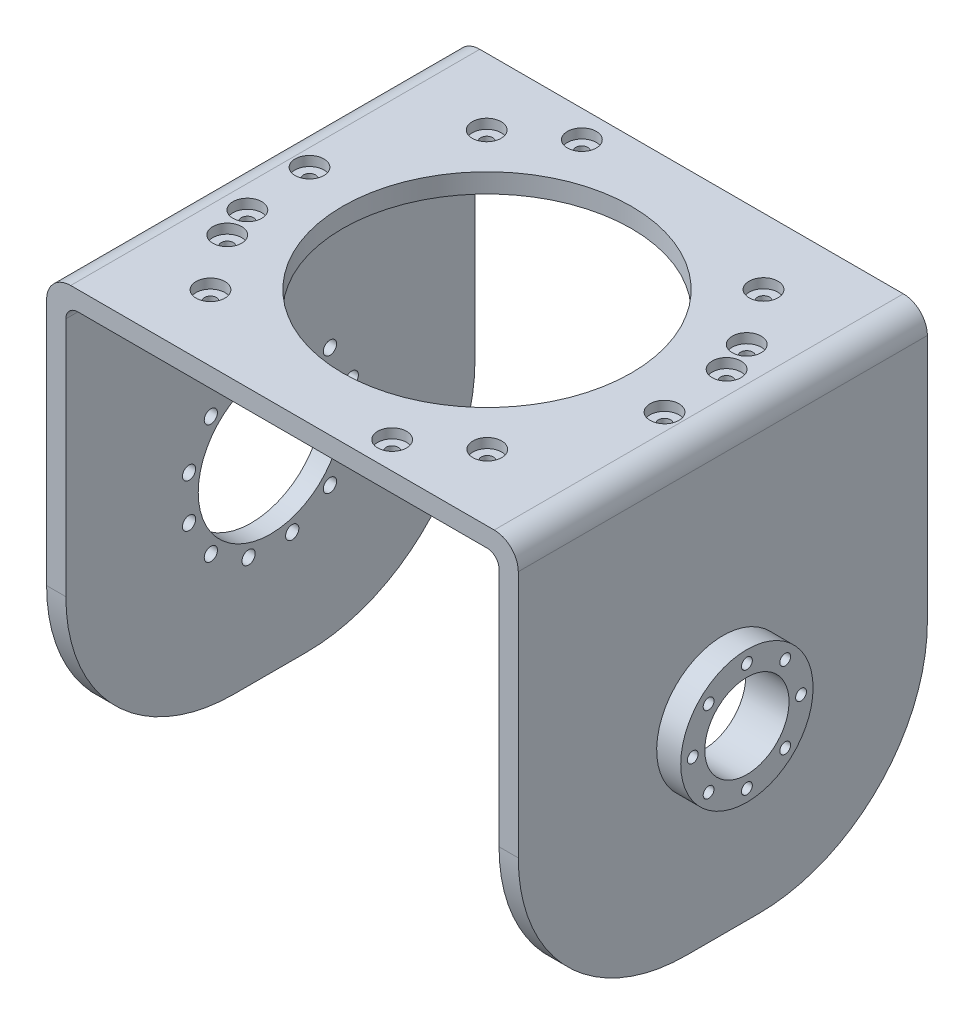
SolidWorks part; units mm, degrees
material "6061 合金"
ref_plane "前视基准面" through (0, 0, 0) normal (0, 0, 1) x (1, 0, 0)
ref_plane "上视基准面" through (0, 0, 0) normal (0, 1, 0) x (1, 0, 0)
ref_plane "右视基准面" through (0, 0, 0) normal (1, 0, 0) x (0, 0, -1)
other "Configuration Table"
sketch "草图1" plane through (0, 0, 0) normal (0, 0, 1) x (1, 0, 0)
  line L0 (-180, 0) -> (0, 0)
  line L1 (0, 0) -> (0, -175)
  line L3 (8, -175) -> (8, 8)
  line L4 (8, 8) -> (-180, 8)
  line L6 (0, -175) -> (8, -175)
  line L12 (-180, 8) -> (-188, 8)
  line L13 (-180, 0) -> (-180, -175)
  line L14 (-180, -175) -> (-188, -175)
  line L15 (-188, 8) -> (-188, -175)
  dimension "D1" = 8
  dimension "D2" = 8
  dimension "D4" = 180
  dimension "D5" = 183
  dimension "D6" = 8
  dimension "D8" = 8
extrude "凸台-拉伸1" add sketch "草图1" along normal blind 170
sketch "草图2" plane through (0, 8, 0) normal (0, 1, 0) x (1, 0, 0)
  line L0 (-216.3195, -85) -> (51.5119, -85) construction
  line L1 (8, -170) -> (-188, -170) construction
  line L2 (8, 0) -> (-188, 0) construction
  line L7 (-90, -75.3242) -> (-90, -92.2023) construction
  line L8 (8, -170) -> (8, 0) construction
  line L9 (-188, -170) -> (-188, 0) construction
  circle A2 centre (-90, -85) radius 60
  dimension "D3" = 120
extrude "切除-拉伸1" cut sketch "草图2" against normal blind 180 contours A2 L0 | L0 A2
sketch "草图3" plane through (8, 0, 0) normal (1, 0, 0) x (0, 0, -1)
  line L0 (-85, 25.6845) -> (-85, -173.3318) construction
  line L1 (0, -175) -> (0, 8) construction
  line L2 (-170, -175) -> (-170, 8) construction
  line L3 (-170, -175) -> (0, -175) construction
  line L4 (0, 0) -> (-209.686, 0) construction
  circle A0 centre (-85, -95) radius 17.5
  dimension "D1" = 35
  dimension "D2" = 80
extrude "切除-拉伸2" cut sketch "草图3" against normal through all both and the other way through all contours A0
fillet "圆角1" radius 70 4 edges at (-184, -175, 170) (-184, -175, 0) (4, -175, 0) (4, -175, 170)
fillet "圆角2" radius 5 2 edges at (-180, 0, 85) (0, 0, 85)
fillet "圆角3" radius 10 2 edges at (8, 8, 85) (-188, 8, 85)
sketch "草图6" plane through (-188, 0, 0) normal (-1, 0, 0) x (0, 0, 1)
  circle A0 centre (85, -95) radius 30
  dimension "D1" = 60
extrude "切除-拉伸6" cut sketch "草图6" against normal blind 39
sketch "草图7" plane through (0, 0, 0) normal (-1, 0, 0) x (0, 0, 1)
  circle A0 centre (85, -95) radius 13
  dimension "D1" = 26
extrude "切除-拉伸7" [suppressed] cut sketch "草图7" against normal blind 0.7
sketch "草图8" plane through (8, 0, 0) normal (1, 0, 0) x (0, 0, -1)
  line L0 (-85, -95) -> (-13.3452, -95) construction
  line L1 (-85, -95) -> (-143.0331, -95) construction
  circle A0 centre (-55, -95) radius 2.5
  circle A1 centre (-115, -95) radius 2.5
  dimension "D1" = 5
  dimension "D2" = 5
  dimension "D3" = 30
  dimension "D4" = 30
extrude "切除-拉伸8" [suppressed] cut sketch "草图8" against normal blind 10
sketch "草图9" [suppressed] plane through (8, 0, 0) normal (1, 0, 0) x (0, 0, -1)
  circle A0 centre (-55, -95) radius 6
  circle A1 centre (-115, -95) radius 6
  dimension "D1" = 12
  dimension "D2" = 12
extrude "切除-拉伸9" [suppressed] cut sketch "草图9" against normal blind 4
sketch "草图10" plane through (0, 0, 0) normal (0, -1, 0) x (1, 0, 0)
  arc A0 (-173.1989, 76.7742) -> (-168.6673, 78.8872) centre (-170.9331, 77.8307) ccw construction
  arc A1 (-149.7806, 26.5535) -> (-145.249, 28.6665) centre (-147.5148, 27.61) ccw construction
  arc A2 (-126.5235, 10.2687) -> (-121.992, 12.3818) centre (-124.2577, 11.3252) ccw construction
  arc A3 (-113.38, 5.4849) -> (-108.8485, 7.598) centre (-111.1143, 6.5414) ccw construction
  arc A4 (-85.0965, 3.0104) -> (-80.5649, 5.1235) centre (-82.8307, 4.0669) ccw construction
  arc A5 (-34.8758, 26.4287) -> (-30.3442, 28.5418) centre (-32.61, 27.4852) ccw construction
  arc A6 (-13.8072, 62.8292) -> (-9.2756, 64.9423) centre (-11.5414, 63.8857) ccw construction
  arc A7 (-18.591, 49.6857) -> (-14.0595, 51.7988) centre (-16.3252, 50.7423) ccw construction
  arc A8 (-6.8011, 93.2258) -> (-11.3327, 91.1128) centre (-9.0669, 92.1693) ccw construction
  arc A9 (-30.2194, 143.4465) -> (-34.751, 141.3335) centre (-32.4852, 142.39) ccw construction
  arc A10 (-53.4765, 159.7313) -> (-58.008, 157.6182) centre (-55.7423, 158.6748) ccw construction
  arc A11 (-66.62, 164.5151) -> (-71.1515, 162.402) centre (-68.8857, 163.4586) ccw construction
  arc A12 (-94.9035, 166.9896) -> (-99.4351, 164.8765) centre (-97.1693, 165.9331) ccw construction
  arc A13 (-145.1242, 143.5713) -> (-149.6558, 141.4582) centre (-147.39, 142.5148) ccw construction
  arc A14 (-161.409, 120.3143) -> (-165.9405, 118.2012) centre (-163.6748, 119.2577) ccw construction
  arc A15 (-166.1928, 107.1708) -> (-170.7244, 105.0577) centre (-168.4586, 106.1143) ccw construction
  arc A16 (-173.1989, 76.7742) -> (-168.6673, 78.8872) centre (-170.9331, 77.8307) ccw construction
  arc A17 (-149.7806, 26.5535) -> (-145.249, 28.6665) centre (-147.5148, 27.61) ccw construction
  arc A18 (-126.5235, 10.2687) -> (-121.992, 12.3818) centre (-124.2577, 11.3252) ccw construction
  arc A19 (-113.38, 5.4849) -> (-108.8485, 7.598) centre (-111.1143, 6.5414) ccw construction
  arc A20 (-85.0965, 3.0104) -> (-80.5649, 5.1235) centre (-82.8307, 4.0669) ccw construction
  arc A21 (-34.8758, 26.4287) -> (-30.3442, 28.5418) centre (-32.61, 27.4852) ccw construction
  arc A22 (-13.8072, 62.8292) -> (-9.2756, 64.9423) centre (-11.5414, 63.8857) ccw construction
  arc A23 (-18.591, 49.6857) -> (-14.0595, 51.7988) centre (-16.3252, 50.7423) ccw construction
  arc A24 (-6.8011, 93.2258) -> (-11.3327, 91.1128) centre (-9.0669, 92.1693) ccw construction
  arc A25 (-30.2194, 143.4465) -> (-34.751, 141.3335) centre (-32.4852, 142.39) ccw construction
  arc A26 (-53.4765, 159.7313) -> (-58.008, 157.6182) centre (-55.7423, 158.6748) ccw construction
  arc A27 (-66.62, 164.5151) -> (-71.1515, 162.402) centre (-68.8857, 163.4586) ccw construction
  arc A28 (-94.9035, 166.9896) -> (-99.4351, 164.8765) centre (-97.1693, 165.9331) ccw construction
  arc A29 (-145.1242, 143.5713) -> (-149.6558, 141.4582) centre (-147.39, 142.5148) ccw construction
  arc A30 (-161.409, 120.3143) -> (-165.9405, 118.2012) centre (-163.6748, 119.2577) ccw construction
  arc A31 (-166.1928, 107.1708) -> (-170.7244, 105.0577) centre (-168.4586, 106.1143) ccw construction
  circle A32 centre (-32.4852, 142.39) radius 2.5
  circle A33 centre (-55.7423, 158.6748) radius 2.5
  circle A34 centre (-68.8857, 163.4586) radius 2.5
  circle A35 centre (-147.39, 142.5148) radius 2.5
  circle A36 centre (-163.6748, 119.2577) radius 2.5
  circle A37 centre (-168.4586, 106.1143) radius 2.5
  circle A38 centre (-170.9331, 77.8307) radius 2.5
  circle A40 centre (-147.5148, 27.61) radius 2.5
  circle A41 centre (-124.2577, 11.3252) radius 2.5
  circle A42 centre (-111.1143, 6.5414) radius 2.5
  circle A44 centre (-32.61, 27.4852) radius 2.5
  circle A45 centre (-16.3252, 50.7423) radius 2.5
  circle A46 centre (-11.5414, 63.8857) radius 2.5
  circle A47 centre (-9.0669, 92.1693) radius 2.5
  dimension "D1" = 5
extrude "切除-拉伸10" cut sketch "草图10" against normal blind 10 contours A33 | A32 | A47 | A46 | A45 | A44 | A41 | A40 | A38 | A37 | A36 | A35
sketch "草图11" plane through (0, 8, 0) normal (0, 1, 0) x (1, 0, 0)
  circle A1 centre (-32.61, -27.4852) radius 6
  circle A2 centre (-16.3252, -50.7423) radius 6
  circle A3 centre (-11.5414, -63.8857) radius 6
  circle A4 centre (-9.0669, -92.1693) radius 6
  circle A5 centre (-32.4852, -142.39) radius 6
  circle A6 centre (-55.7423, -158.6748) radius 6
  circle A8 centre (-147.39, -142.5148) radius 6
  circle A9 centre (-163.6748, -119.2577) radius 6
  circle A10 centre (-168.4586, -106.1143) radius 6
  circle A11 centre (-170.9331, -77.8307) radius 6
  circle A12 centre (-147.5148, -27.61) radius 6
  circle A13 centre (-124.2577, -11.3252) radius 6
  circle M2 centre (-55.7423, -158.6748) radius 2.5
  circle M4 centre (-147.39, -142.5148) radius 2.5
  circle M5 centre (-163.6748, -119.2577) radius 2.5
  circle M6 centre (-168.4586, -106.1143) radius 2.5
  circle M7 centre (-170.9331, -77.8307) radius 2.5
  circle M8 centre (-147.5148, -27.61) radius 2.5
  circle M9 centre (-124.2577, -11.3252) radius 2.5
  circle M11 centre (-32.61, -27.4852) radius 2.5
  circle M12 centre (-16.3252, -50.7423) radius 2.5
  circle M13 centre (-11.5414, -63.8857) radius 2.5
  circle M14 centre (-9.0669, -92.1693) radius 2.5
  circle M15 centre (-32.4852, -142.39) radius 2.5
  dimension "D1" = 12
extrude "切除-拉伸11" cut sketch "草图11" against normal blind 4 contours A5 M15 | A6 M2 | A8 M4 | A9 M5 | A10 M6 | A11 M7 | A12 M8 | A13 M9 | A1 M11 | A2 M12 | A3 M13 | A4 M14
sketch "草图12" plane through (-188, 0, 0) normal (-1, 0, 0) x (0, 0, 1)
  line L0 (85, -95) -> (85, -143.8801) construction
  line L1 (85, -95) -> (97.9809, -143.4455) construction
  circle A0 centre (94.0587, -128.8074) radius 2.75
  circle A1 centre (75.9413, -128.8074) radius 2.75
  circle A2 centre (60.2513, -119.7487) radius 2.75
  circle A3 centre (51.1926, -104.0587) radius 2.75
  circle A4 centre (51.1926, -85.9413) radius 2.75
  circle A5 centre (60.2513, -70.2513) radius 2.75
  circle A6 centre (75.9413, -61.1926) radius 2.75
  circle A7 centre (94.0587, -61.1926) radius 2.75
  circle A8 centre (109.7487, -70.2513) radius 2.75
  circle A9 centre (118.8074, -85.9413) radius 2.75
  circle A10 centre (118.8074, -104.0587) radius 2.75
  circle A11 centre (109.7487, -119.7487) radius 2.75
  point P31 (85, -95)
  dimension "D2" = 5.5
  dimension "D1" = 15
  dimension "D3" = 35
  dimension "D4" = 12
extrude "切除-拉伸12" cut sketch "草图12" against normal blind 10
sketch "草图14" plane through (8, 0, 0) normal (1, 0, 0) x (0, 0, -1)
  circle A0 centre (-85, -95) radius 27.5
  circle A1 centre (-85, -95) radius 17.5 construction
  circle A2 centre (-85, -95) radius 17.5
  dimension "D1" = 55
extrude "凸台-拉伸2" add sketch "草图14" along normal blind 10
sketch "草图13" plane through (8, 0, 0) normal (1, 0, 0) x (0, 0, -1)
  line L0 (-85, -95) -> (-85, -50) construction
  circle A0 centre (-85, -95) radius 22.5 construction
  circle A1 centre (-85, -72.5) radius 2.25
  circle A2 centre (-69.0901, -79.0901) radius 2.25
  circle A3 centre (-62.5, -95) radius 2.25
  circle A4 centre (-69.0901, -110.9099) radius 2.25
  circle A5 centre (-85, -117.5) radius 2.25
  circle A6 centre (-100.9099, -110.9099) radius 2.25
  circle A7 centre (-107.5, -95) radius 2.25
  circle A8 centre (-100.9099, -79.0901) radius 2.25
  point P22 (-85, -95)
  dimension "D1" = 45
  dimension "D2" = 4.5
  dimension "D3" = 8
extrude "切除-拉伸13" cut sketch "草图13" against normal mid plane 30
